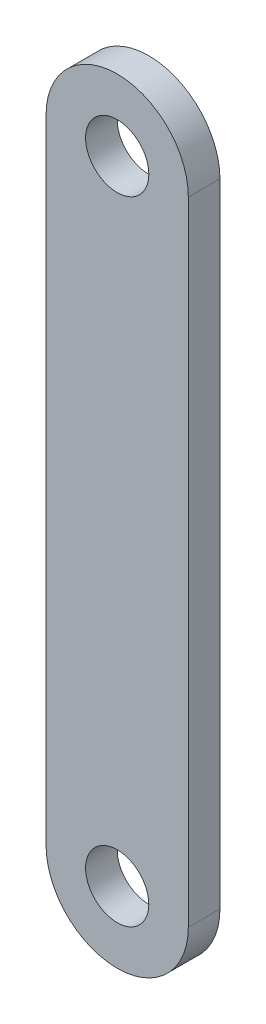
SolidWorks part; units mm, degrees
ref_plane "Alzado" through (0, 0, 0) normal (0, 0, 1) x (1, 0, 0)
ref_plane "Planta" through (0, 0, 0) normal (0, 1, 0) x (1, 0, 0)
ref_plane "Vista lateral" through (0, 0, 0) normal (1, 0, 0) x (0, 0, -1)
sketch "Croquis1" plane through (0, 0, 0) normal (0, 0, 1) x (1, 0, 0)
  line L0 (-22.5, 0) -> (-22.5, -200)
  line L1 (22.5, 0) -> (22.5, -200)
  circle A0 centre (0, 0) radius 10
  arc A1 (22.5, 0) -> (-22.5, 0) centre (0, 0) ccw
  arc A2 (-22.5, -200) -> (22.5, -200) centre (0, -200) ccw
  circle A3 centre (0, 0) radius 22.5 construction
  circle A4 centre (0, -200) radius 10
  dimension "D2" = 45
extrude "Saliente-Extruir1" add sketch "Croquis1" along normal blind 10
